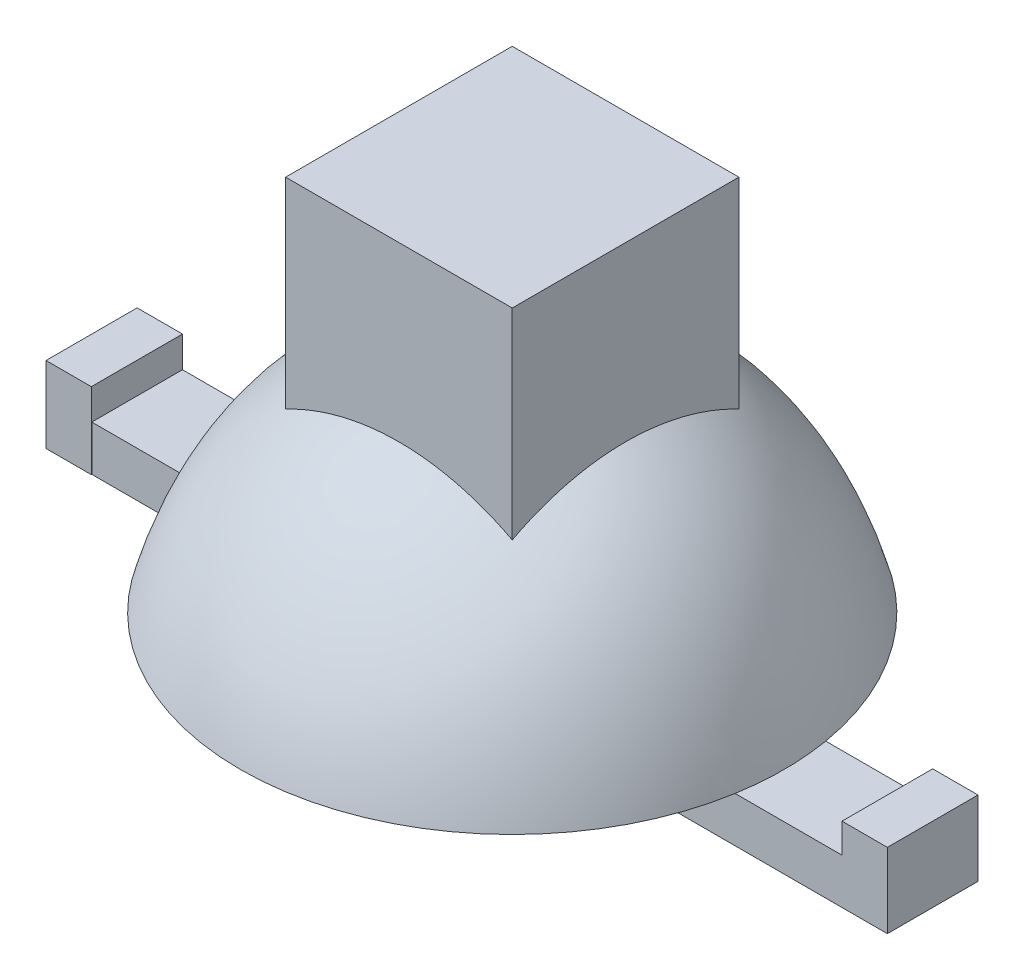
SolidWorks part; units mm, degrees
ref_plane "前视基准面" through (0, 0, 0) normal (0, 0, 1) x (1, 0, 0)
ref_plane "上视基准面" through (0, 0, 0) normal (0, 1, 0) x (1, 0, 0)
ref_plane "右视基准面" through (0, 0, 0) normal (1, 0, 0) x (0, 0, -1)
sketch "草图1" plane through (0, 0, 0) normal (0, 1, 0) x (1, 0, 0)
  line L1 (-2.5, -2.5) -> (2.5, -2.5)
  line L2 (-2.5, -2.5) -> (-2.5, 2.5)
  line L3 (-2.5, 2.5) -> (2.5, 2.5)
  line L4 (2.5, -2.5) -> (2.5, 2.5)
  line L5 (-2.5, -2.5) -> (2.5, 2.5) construction
  line L6 (-2.5, 2.5) -> (2.5, -2.5) construction
  point P0 (0, 0)
  dimension "D1" = 5
  dimension "5" = 5
extrude "凸台-拉伸1" add sketch "草图1" against normal blind 3 and the other way blind 1.5
sketch "草图2" plane through (0, 0, 0) normal (0, 0, 1) x (1, 0, 0)
  line L2 (0, 0) -> (0, -7.5149) construction
  line L3 (-6, -6.8171) -> (0, -6.8171)
  line L4 (0, -6.8171) -> (0, -1.6132)
  spline S0 degree 2 poles (-6, -6.8171) (-4.7343, -2.1844) (0, -1.6132) knots 0 0 0 1 1 1
  dimension "D1" = 6
revolve "旋转1" add sketch "草图2" angle 360 about L4
sketch "草图3" plane through (0, -6.8171, 0) normal (0, -1, 0) x (1, 0, 0)
  line L1 (-8.275, -1) -> (8.275, -1)
  line L2 (-8.275, -1) -> (-8.275, 1)
  line L3 (-8.275, 1) -> (8.275, 1)
  line L4 (8.275, -1) -> (8.275, 1)
  line L5 (-8.275, -1) -> (8.275, 1) construction
  line L6 (-8.275, 1) -> (8.275, -1) construction
  point P0 (0, 0)
  dimension "D1" = 2
  dimension "D2" = 16.55
extrude "凸台-拉伸2" add sketch "草图3" along normal blind 1
sketch "草图4" plane through (-8.275, 0, 0) normal (-1, 0, 0) x (0, 0, 1)
  line L0 (-1, -7.8171) -> (1.0106, -7.8171)
  line L1 (1.0106, -7.8171) -> (1.0106, -6.135)
  line L2 (1.0106, -6.135) -> (-1, -6.135)
  line L3 (-1, -6.135) -> (-1, -7.8171)
extrude "凸台-拉伸3" add sketch "草图4" along normal blind 1
sketch "草图5" plane through (8.275, 0, 0) normal (1, 0, 0) x (0, 0, -1)
  line L0 (-1, -7.8171) -> (-1, -6.1666)
  line L1 (-1, -7.8171) -> (1, -7.8171)
  line L2 (1, -7.8171) -> (1, -6.1666)
  line L3 (1, -6.1666) -> (-1, -6.1666)
extrude "凸台-拉伸4" add sketch "草图5" along normal blind 1
